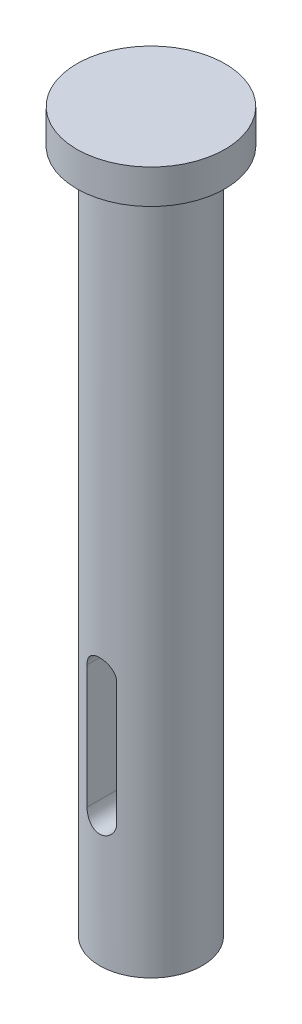
SolidWorks part; units mm, degrees
material "PVC Rigid"
ref_plane "Front Plane" through (0, 0, 0) normal (0, 0, 1) x (1, 0, 0)
ref_plane "Top Plane" through (0, 0, 0) normal (0, 1, 0) x (1, 0, 0)
ref_plane "Right Plane" through (0, 0, 0) normal (1, 0, 0) x (0, 0, -1)
sketch "Sketch1" plane through (0, 0, 0) normal (0, 1, 0) x (1, 0, 0)
  circle A0 centre (0, 0) radius 11.43
  dimension "D1" = 22.86
extrude "Boss-Extrude1" add sketch "Sketch1" along normal blind 160.02
ref_plane "Plane1" through (0, 0, 11.43) normal (0, 0, 1) x (1, 0, 0)
sketch "Sketch2" plane through (0, 0, 11.43) normal (0, 0, 1) x (1, 0, 0)
  line L0 (0, 0) -> (0, 25.4) construction
  line L1 (0, 160.02) -> (0, 59.436) construction
  line L2 (11.43, 160.02) -> (-11.43, 160.02) construction
  line L5 (3.302, 28.702) -> (3.302, 56.134)
  line L7 (-3.302, 28.702) -> (-3.302, 56.134)
  arc A0 (-3.302, 56.134) -> (3.302, 56.134) centre (0, 56.134) cw
  arc A1 (-3.302, 28.702) -> (3.302, 28.702) centre (0, 28.702) ccw
  point P11 (0, 59.436)
  point P18 (0, 25.4)
  dimension "D4" = 3.302
  dimension "D5" = 3.302
  dimension "D1" = 25.4
  dimension "D2" = 34.036
  dimension "D3" = 6.604
extrude "Cut-Extrude1" cut sketch "Sketch2" against normal blind 73.66
sketch "Sketch3" plane through (0, 160.02, 0) normal (0, 1, 0) x (1, 0, 0)
  circle A0 centre (0, 0) radius 16.51
  circle A1 centre (0, 0) radius 11.43
  dimension "D1" = 33.02
extrude "Boss-Extrude2" add sketch "Sketch3" against normal blind 7.62
